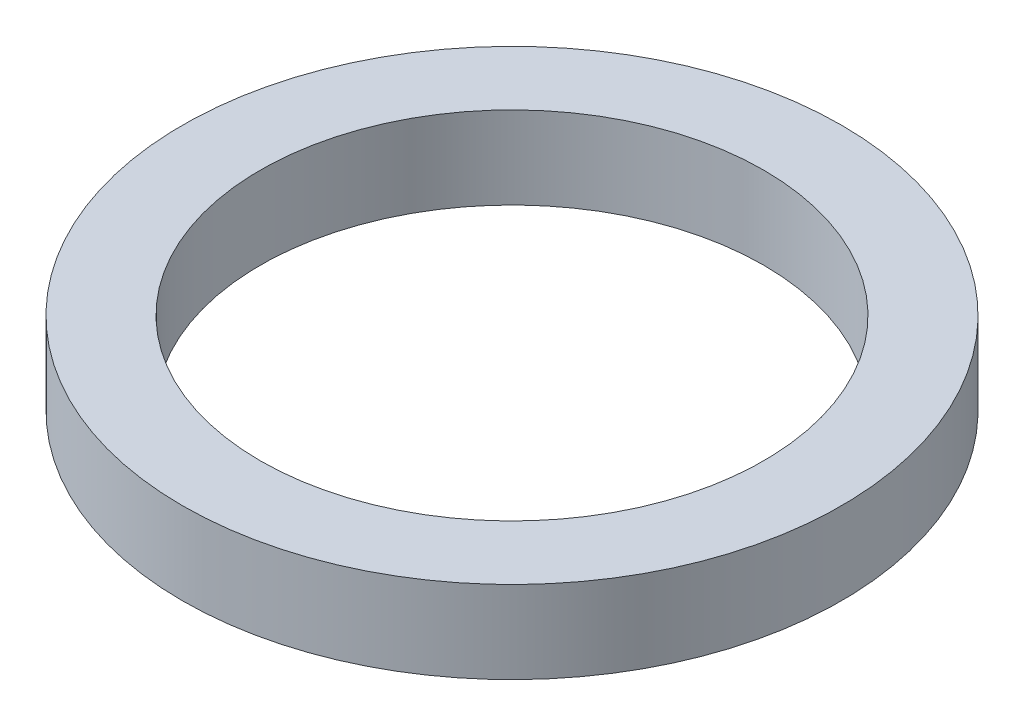
SolidWorks part; units mm, degrees
ref_plane "Front Plane" through (0, 0, 0) normal (0, 0, 1) x (1, 0, 0)
ref_plane "Top Plane" through (0, 0, 0) normal (0, 1, 0) x (1, 0, 0)
ref_plane "Right Plane" through (0, 0, 0) normal (1, 0, 0) x (0, 0, -1)
sketch "Sketch1" plane through (0, 0, 0) normal (0, 1, 0) x (1, 0, 0)
  circle A0 centre (0, 0) radius 36
  circle A1 centre (0, 0) radius 27.5
  dimension "D1" = 55
  dimension "D2" = 72
extrude "Boss-Extrude1" add sketch "Sketch1" along normal blind 9
